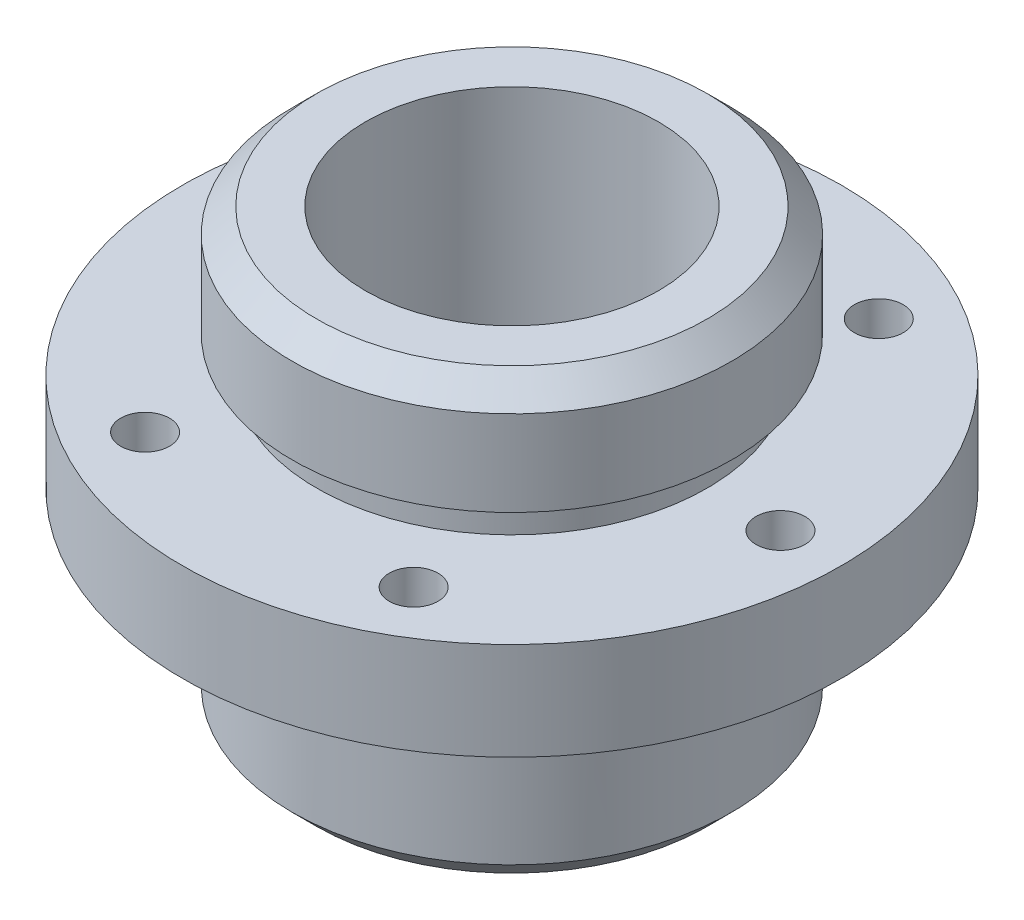
SolidWorks part; units mm, degrees
ref_plane "Front Plane" through (0, 0, 0) normal (0, 0, 1) x (1, 0, 0)
ref_plane "Top Plane" through (0, 0, 0) normal (0, 1, 0) x (1, 0, 0)
ref_plane "Right Plane" through (0, 0, 0) normal (1, 0, 0) x (0, 0, -1)
sketch "Sketch2" plane through (0, 0, 0) normal (0, 0, 1) x (1, 0, 0)
  line L0 (0, 0) -> (-24, 0) construction
  line L1 (-24, 0) -> (-24, 72)
  line L2 (-24, 72) -> (-36, 72)
  line L3 (-36, 72) -> (-36, 54)
  line L4 (-32, 48) -> (-32, 51.426)
  line L5 (0, 0) -> (0, 86.279) construction
  line L6 (-32, 48) -> (-54, 48)
  line L7 (-54, 48) -> (-54, 32)
  line L8 (-54, 32) -> (-32, 32)
  line L11 (-32, 32) -> (-32, 28)
  line L12 (-36, 24) -> (-36, 0)
  line L13 (-36, 0) -> (-24, 0)
  line L14 (-36, 54) -> (-34.8823, 54)
  arc A0 (-32.5588, 52.8127) -> (-34.8823, 54) centre (-35.4412, 50.0392) ccw
  arc A2 (-32, 51.426) -> (-32.5588, 52.8127) centre (-34, 51.426) ccw
  arc A3 (-36, 24) -> (-32, 28) centre (-36, 28) ccw
  dimension "D2" = 24
  dimension "D8" = 32
  dimension "D11" = 4
  dimension "D14" = 6
  dimension "D15" = 4
  dimension "D16" = 2
  dimension "D3" = 24
  dimension "D4" = 54
  dimension "D5" = 16
  dimension "D6" = 36
  dimension "D7" = 12
  dimension "D9" = 36
  dimension "D10" = 32
  dimension "D12" = 32
  dimension "D13" = 72
revolve "Revolve2" add sketch "Sketch2" angle 360 about L5
chamfer "Chamfer4" distance 4 angle 45 2 edges at (0, 0, -36) (0, 72, -36)
sketch "Sketch3" plane through (0, 48, 0) normal (0, 1, 0) x (1, 0, 0)
  circle A0 centre (0, 0) radius 44 construction
  circle A1 centre (44, 0) radius 4
  circle A2 centre (22, -38.1051) radius 4
  circle A3 centre (-22, -38.1051) radius 4
  circle A4 centre (-44, 0) radius 4
  circle A5 centre (-22, 38.1051) radius 4
  circle A6 centre (22, 38.1051) radius 4
  point P17 (0, 0)
  dimension "D1" = 6
extrude "Cut-Extrude1" cut sketch "Sketch3" against normal up to next
